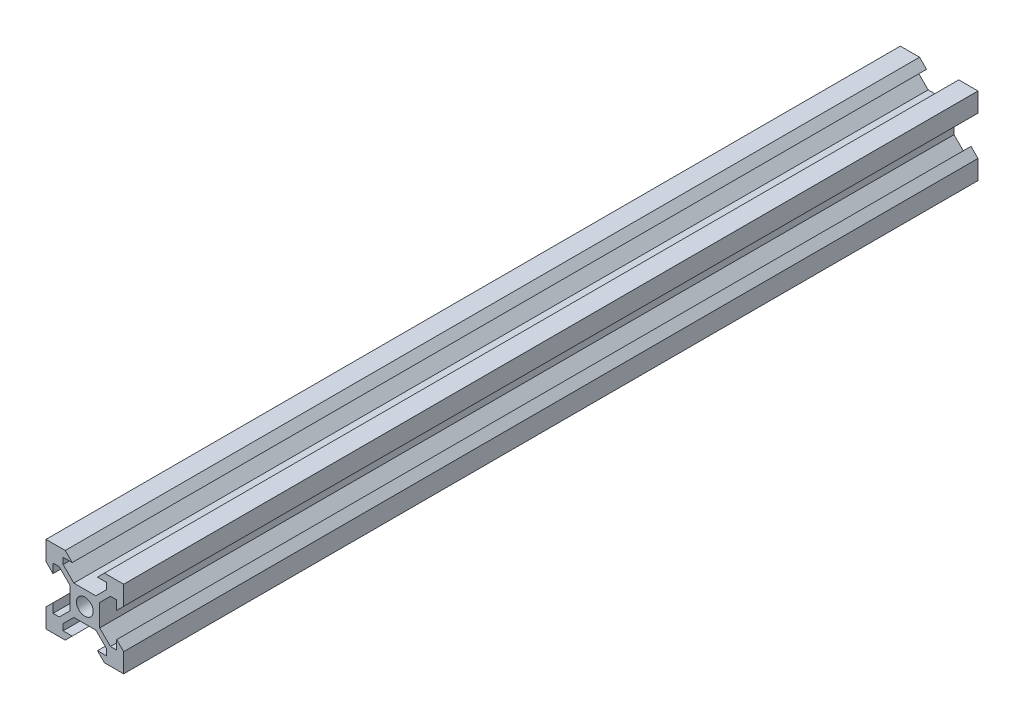
SolidWorks part; units mm, degrees
ref_plane "Alzado" through (0, 0, 0) normal (0, 0, 1) x (1, 0, 0)
ref_plane "Planta" through (0, 0, 0) normal (0, 1, 0) x (1, 0, 0)
ref_plane "Vista lateral" through (0, 0, 0) normal (1, 0, 0) x (0, 0, -1)
sketch "Croquis1" plane through (0, 0, 0) normal (0, 0, 1) x (1, 0, 0)
  line L0 (0, 0) -> (0, -20) construction
  line L2 (0, 0) -> (0, -0.5674)
  line L5 (6.175, -7.1649) -> (6.175, -12.8351)
  line L6 (7.1649, -13.825) -> (12.8351, -13.825)
  line L7 (13.825, -7.1649) -> (13.825, -12.8351)
  line L8 (7.1649, -6.175) -> (12.8351, -6.175)
  line L9 (6.175, -13.825) -> (13.825, -13.825) construction
  line L10 (13.825, -6.175) -> (13.825, -13.825) construction
  line L12 (10, -10) -> (32.1172, -10) construction
  line L13 (13.25, -18.2) -> (15.05, -20)
  line L14 (20, -20) -> (15.6, -20)
  line L15 (20, -20) -> (20, -15.6)
  line L16 (18.2, -15.6) -> (16.5899, -15.6)
  line L32 (15.6, -18.2) -> (15.6, -16.5899)
  line L33 (10, -10) -> (10, -23.2493) construction
  line L34 (4.4, -18.2) -> (4.4, -16.5899)
  line L35 (7.1649, -13.825) -> (4.4, -16.5899)
  line L36 (15.6, -18.2) -> (13.25, -18.2)
  line L38 (15.6, -20) -> (15.05, -20)
  line L40 (15.05, -20) -> (20, -20)
  line L41 (0, -20) -> (20, -20) construction
  line L42 (6.175, -12.8351) -> (3.4101, -15.6)
  line L43 (18.2, -13.25) -> (20, -15.05)
  line L44 (20, -20) -> (18.2, -20)
  line L45 (20, -20) -> (20, -15.05)
  line L48 (20, -15.05) -> (20, -20)
  line L49 (20, 0) -> (20, -20) construction
  line L50 (18.2, -15.6) -> (18.2, -13.25)
  line L51 (12.8351, -13.825) -> (15.6, -16.5899)
  line L52 (13.825, -12.8351) -> (16.5899, -15.6)
  line L53 (1.8, -15.6) -> (3.4101, -15.6)
  line L54 (1.8, -15.6) -> (1.8, -13.25)
  line L55 (1.8, -13.25) -> (0, -15.05)
  line L56 (0, 0) -> (20, 0) construction
  line L57 (0, -20) -> (0, -15.6)
  line L58 (0, -15.6) -> (0, -15.05)
  line L59 (0, -20) -> (4.4, -20)
  line L60 (0, -20) -> (4.95, -20)
  line L61 (6.75, -18.2) -> (4.95, -20)
  line L62 (4.4, -18.2) -> (6.75, -18.2)
  line L63 (1.8, -4.4) -> (3.4101, -4.4)
  line L64 (6.175, -7.1649) -> (3.4101, -4.4)
  line L65 (7.1649, -6.175) -> (4.4, -3.4101)
  line L66 (4.4, -1.8) -> (4.4, -3.4101)
  line L67 (4.4, -1.8) -> (6.75, -1.8)
  line L68 (6.75, -1.8) -> (4.95, 0)
  line L69 (0, 0) -> (4.4, 0)
  line L70 (4.4, 0) -> (4.95, 0)
  line L71 (0, 0) -> (0, -4.4)
  line L72 (0, 0) -> (0, -4.95)
  line L73 (1.8, -6.75) -> (0, -4.95)
  line L74 (1.8, -4.4) -> (1.8, -6.75)
  line L75 (15.6, -1.8) -> (15.6, -3.4101)
  line L76 (12.8351, -6.175) -> (15.6, -3.4101)
  line L77 (13.825, -7.1649) -> (16.5899, -4.4)
  line L78 (18.2, -4.4) -> (16.5899, -4.4)
  line L79 (18.2, -4.4) -> (18.2, -6.75)
  line L80 (18.2, -6.75) -> (20, -4.95)
  line L81 (20, 0) -> (20, -4.4)
  line L82 (20, -4.4) -> (20, -4.95)
  line L83 (20, 0) -> (15.6, 0)
  line L84 (20, 0) -> (15.05, 0)
  line L85 (13.25, -1.8) -> (15.05, 0)
  line L86 (15.6, -1.8) -> (13.25, -1.8)
  line L87 (6.175, -6.175) -> (13.825, -6.175) construction
  line L88 (6.175, -6.175) -> (6.175, -13.825) construction
  circle A0 centre (10, -10) radius 2.15
  point P69 (10, -10)
  dimension "D3" = 4.3
  dimension "D2" = 4
  dimension "D11" = 4.4
  dimension "D15" = 4.4
  dimension "D16" = 6.75
extrude "BoschBase" add sketch "Croquis1" along normal blind 220 contours L86 L75 L76 L8 L65 L66 L67 L68 L70 L69 L2 L71 L72 L73 L74 L63 L64 L5 L42 L53 L54 L55 L58 L57 L59 L60 L61 L62 L34 L35 L6 L51 L32 L36 L13 L38 L40 L14 L15 L45 L43 L50 L16 L52 L7 L77 L78 L79 L80 L82 L81
